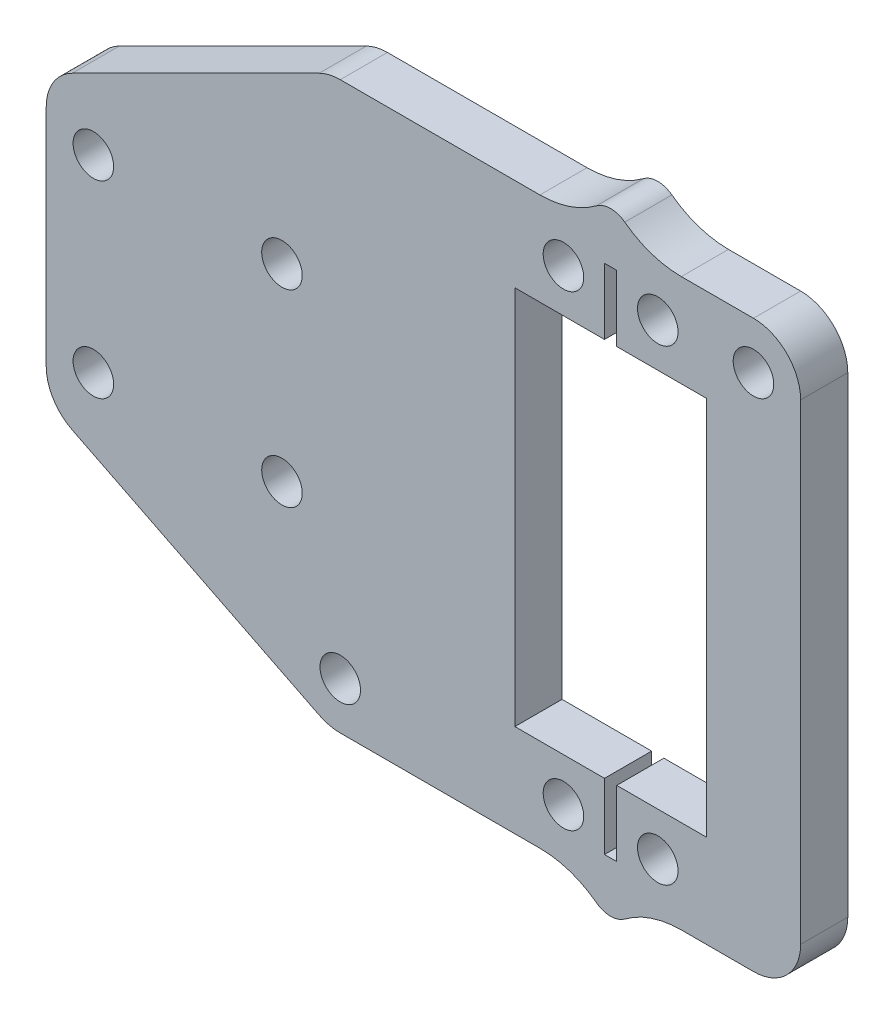
SolidWorks part; units mm, degrees
material "ﾎﾟﾘｴﾁﾚﾝｲﾐﾝ(PEI)"
ref_plane "正面" through (0, 0, 0) normal (0, 0, 1) x (1, 0, 0)
ref_plane "平面" through (0, 0, 0) normal (0, 1, 0) x (1, 0, 0)
ref_plane "右側面" through (0, 0, 0) normal (1, 0, 0) x (0, 0, -1)
sketch "ｽｹｯﾁ1" plane through (0, 0, 0) normal (0, 0, 1) x (1, 0, 0)
  line L0 (0, 24.75) -> (0, -24.75) construction
  line L1 (-5, 24.75) -> (5, 24.75) construction
  line L2 (-5, 24.75) -> (-5, -24.75) construction
  line L3 (-5, -24.75) -> (5, -24.75) construction
  line L4 (5, 24.75) -> (5, -24.75) construction
  line L5 (-5, 24.75) -> (5, -24.75) construction
  line L6 (-5, -24.75) -> (5, 24.75) construction
  line L7 (-5, 0) -> (5, 0) construction
  line L8 (0.65, -27.15) -> (0.65, -20.15)
  line L9 (-10.15, 20.15) -> (10.15, 20.15)
  line L10 (-10.15, 20.15) -> (-10.15, -20.15)
  line L11 (-10.15, -20.15) -> (10.15, -20.15)
  line L12 (10.15, 20.15) -> (10.15, -20.15)
  line L13 (-10.15, 20.15) -> (10.15, -20.15) construction
  line L14 (-10.15, -20.15) -> (10.15, 20.15) construction
  line L15 (-0.65, 27.15) -> (0.65, 27.15)
  line L16 (-0.65, 27.15) -> (-0.65, 20.15)
  line L17 (-0.65, 20.15) -> (0.65, 20.15)
  line L18 (0.65, 27.15) -> (0.65, 20.15)
  line L19 (-0.65, 27.15) -> (0.65, 20.15) construction
  line L20 (-0.65, 20.15) -> (0.65, 27.15) construction
  line L21 (-0.65, -27.15) -> (-0.65, -20.15)
  line L22 (-0.65, -27.15) -> (0.65, -27.15)
  line L23 (10.15, 0) -> (-51.75, 0) construction
  line L25 (-59.85, 30) -> (20.15, 30)
  line L26 (-59.85, 30) -> (-59.85, -30)
  line L27 (-59.85, -30) -> (20.15, -30)
  line L28 (20.15, 30) -> (20.15, -30)
  line L29 (-59.85, 30) -> (20.15, -30) construction
  line L30 (-59.85, -30) -> (20.15, 30) construction
  circle A0 centre (-5, 24.75) radius 2.15
  circle A1 centre (5, 24.75) radius 2.15
  circle A2 centre (5, -24.75) radius 2.15
  circle A3 centre (-5, -24.75) radius 2.15
  point P0 (0, 0)
  point P14 (0, 0)
  point P19 (0, 23.65)
  point P29 (-19.85, 0)
  dimension "D3" = 4.3
  dimension "D1" = 10
  dimension "D2" = 49.5
  dimension "D4" = 20.3
  dimension "D5" = 40.3
  dimension "D6" = 1.3
  dimension "D7" = 7
  dimension "D8" = 60
  dimension "D9" = 10
  dimension "D10" = 80
extrude "ﾎﾞｽ - 押し出し1" add sketch "ｽｹｯﾁ1" along normal blind 5 contours L28 L25 L26 L27 A1 A0 L22 L21 L11 L10 L9 L16 L15 L18 L12 L8 A2 A3
sketch "ｽｹｯﾁ2" plane through (0, 0, 5) normal (0, 0, 1) x (1, 0, 0)
  line L0 (-59.85, 0) -> (20.15, 0) construction
  line L1 (-59.85, 30) -> (-59.85, -30) construction
  line L2 (20.15, 30) -> (20.15, -30) construction
  line L3 (-54.85, 0) -> (-54.85, 10) construction
  line L4 (-54.85, 10) -> (-34.85, 10) construction
  circle A0 centre (-54.85, 10) radius 2.15
  circle A1 centre (-54.85, -10) radius 2.15
  circle A2 centre (-34.85, 10) radius 2.15
  circle A3 centre (-34.85, -10) radius 2.15
  dimension "D1" = 4.3
  dimension "D2" = 5
  dimension "D3" = 20
  dimension "D5" = 20
  dimension "D4" = 2
extrude "ｶｯﾄ - 押し出し1" cut sketch "ｽｹｯﾁ2" against normal through all
sketch "ｽｹｯﾁ3" plane through (0, 0, 5) normal (0, 0, 1) x (1, 0, 0)
  line L0 (-59.85, 30) -> (20.15, 30) construction
  line L1 (20.15, 30) -> (20.15, -30) construction
  line L6 (20.15, -30) -> (20.15, 30)
  line L7 (20.15, 30) -> (-59.85, 30)
  line L8 (-59.85, 30) -> (-59.85, -30)
  line L9 (-59.85, -30) -> (20.15, -30)
  line L10 (20.15, -30) -> (20.15, 30)
  line L11 (20.15, 30) -> (-59.85, 30)
  line L12 (-59.85, 30) -> (-59.85, -30)
  line L13 (-59.85, -30) -> (20.15, -30)
  circle A0 centre (15.15, 25) radius 5
  circle A1 centre (15.15, 25) radius 2.15
  line M12 (20.15, 30) -> (-59.85, 30)
  dimension "D1" = 10
  dimension "D2" = 4.3
  dimension "D3" = 0
extrude "ｶｯﾄ - 押し出し2" cut sketch "ｽｹｯﾁ3" against normal through all contours A1 | A0 L10 M12
sketch "ｽｹｯﾁ4" plane through (0, 0, 5) normal (0, 0, 1) x (1, 0, 0)
  line L0 (0, 0) -> (-59.85, 0) construction
  line L1 (-59.85, 30) -> (-59.85, -30) construction
  line L2 (-59.85, 15.0017) -> (-29.85, 30)
  line L3 (-59.85, 30) -> (15.15, 30) construction
  line L4 (-59.85, -15.0017) -> (-29.85, -30)
  line L9 (20.15, -30) -> (20.15, 25)
  line L10 (15.15, 30) -> (-59.85, 30)
  line L11 (-59.85, 30) -> (-59.85, -30)
  line L12 (-59.85, -30) -> (20.15, -30)
  line L13 (20.15, -30) -> (20.15, 25)
  line L14 (15.15, 30) -> (-59.85, 30)
  line L15 (-59.85, 30) -> (-59.85, -30)
  line L16 (-59.85, -30) -> (20.15, -30)
  arc A1 (20.15, 25) -> (15.15, 30) centre (15.15, 25) ccw
  arc A2 (20.15, 25) -> (15.15, 30) centre (15.15, 25) ccw
  line M31 (15.15, 30) -> (-59.85, 30)
  line M32 (-59.85, 30) -> (-59.85, -30)
  line M33 (-59.85, -30) -> (20.15, -30)
  dimension "D1" = 15.0017
  dimension "D2" = 30
  dimension "D3" = 0
extrude "ｶｯﾄ - 押し出し3" cut sketch "ｽｹｯﾁ4" against normal through all contours L2 M32 M31 | L4 M32 M33
fillet "ﾌｨﾚｯﾄ1" radius 5 1 edges at (20.15, -30, 2.5)
sketch "ｽｹｯﾁ5" plane through (0, 0, 5) normal (0, 0, 1) x (1, 0, 0)
  line L0 (-29.85, -30) -> (15.15, -30) construction
  line L1 (-59.85, -15.0017) -> (-29.85, -30) construction
  circle A0 centre (-28.6698, -25) radius 5 construction
  circle A1 centre (-28.6698, -25) radius 2.15
  dimension "D1" = 10
  dimension "D2" = 4.3
extrude "ｶｯﾄ - 押し出し4" cut sketch "ｽｹｯﾁ5" against normal through all
fillet "ﾌｨﾚｯﾄ2" radius 5 4 edges at (-29.85, -30, 2.5) (-59.85, -15.0017, 2.5) (-29.85, 30, 2.5) (-59.85, 15.0017, 2.5)
sketch "ｽｹｯﾁ6" plane through (0, 0, 5) normal (0, 0, 1) x (1, 0, 0)
  line L0 (0, 0) -> (0, 47.5768) construction
  line L2 (-10.15, 0) -> (10.15, 0) construction
  line L7 (-57.0859, -16.3836) -> (-30.9056, -29.4722)
  line L8 (-28.6698, -30) -> (15.15, -30)
  line L9 (20.15, -25) -> (20.15, 25)
  line L10 (15.15, 30) -> (-28.6698, 30)
  line L11 (-30.9056, 29.4722) -> (-57.0859, 16.3836)
  line L12 (-59.85, 11.9114) -> (-59.85, -11.9114)
  line L13 (-57.0859, -16.3836) -> (-30.9056, -29.4722)
  line L14 (-28.6698, -30) -> (15.15, -30)
  line L15 (20.15, -25) -> (20.15, 25)
  line L16 (15.15, 30) -> (-28.6698, 30)
  line L17 (-30.9056, 29.4722) -> (-57.0859, 16.3836)
  line L18 (-59.85, 11.9114) -> (-59.85, -11.9114)
  line L26 (-0.65, -27.15) -> (0.65, -27.15)
  line L27 (-0.65, -20.15) -> (-0.65, -27.15)
  line L28 (-10.15, -20.15) -> (-0.65, -20.15)
  line L29 (-10.15, 20.15) -> (-10.15, -20.15)
  line L30 (-0.65, 20.15) -> (-10.15, 20.15)
  line L31 (-0.65, 27.15) -> (-0.65, 20.15)
  line L32 (0.65, 27.15) -> (-0.65, 27.15)
  line L33 (0.65, 20.15) -> (0.65, 27.15)
  line L34 (10.15, 20.15) -> (0.65, 20.15)
  line L35 (10.15, -20.15) -> (10.15, 20.15)
  line L36 (0.65, -20.15) -> (10.15, -20.15)
  line L37 (0.65, -27.15) -> (0.65, -20.15)
  line L38 (-0.65, -27.15) -> (0.65, -27.15)
  line L39 (-0.65, -20.15) -> (-0.65, -27.15)
  line L40 (-10.15, -20.15) -> (-0.65, -20.15)
  line L41 (-10.15, 20.15) -> (-10.15, -20.15)
  line L42 (-0.65, 20.15) -> (-10.15, 20.15)
  line L43 (-0.65, 27.15) -> (-0.65, 20.15)
  line L44 (0.65, 27.15) -> (-0.65, 27.15)
  line L45 (0.65, 20.15) -> (0.65, 27.15)
  line L46 (10.15, 20.15) -> (0.65, 20.15)
  line L47 (10.15, -20.15) -> (10.15, 20.15)
  line L48 (0.65, -20.15) -> (10.15, -20.15)
  line L49 (0.65, -27.15) -> (0.65, -20.15)
  circle A0 centre (0, 30) radius 2.5
  circle A1 centre (0, -30) radius 2.5
  circle A2 centre (-28.6698, -25) radius 2.15
  circle A3 centre (-28.6698, -25) radius 2.15
  circle A4 centre (-34.85, 10) radius 2.15
  circle A5 centre (-34.85, 10) radius 2.15
  arc A6 (-30.9056, -29.4722) -> (-28.6698, -30) centre (-28.6698, -25) ccw
  arc A7 (15.15, -30) -> (20.15, -25) centre (15.15, -25) ccw
  arc A8 (20.15, 25) -> (15.15, 30) centre (15.15, 25) ccw
  arc A9 (-28.6698, 30) -> (-30.9056, 29.4722) centre (-28.6698, 25) ccw
  arc A10 (-57.0859, 16.3836) -> (-59.85, 11.9114) centre (-54.85, 11.9114) ccw
  arc A11 (-59.85, -11.9114) -> (-57.0859, -16.3836) centre (-54.85, -11.9114) ccw
  arc A12 (-30.9056, -29.4722) -> (-28.6698, -30) centre (-28.6698, -25) ccw
  arc A13 (15.15, -30) -> (20.15, -25) centre (15.15, -25) ccw
  arc A14 (20.15, 25) -> (15.15, 30) centre (15.15, 25) ccw
  arc A15 (-28.6698, 30) -> (-30.9056, 29.4722) centre (-28.6698, 25) ccw
  arc A16 (-57.0859, 16.3836) -> (-59.85, 11.9114) centre (-54.85, 11.9114) ccw
  arc A17 (-59.85, -11.9114) -> (-57.0859, -16.3836) centre (-54.85, -11.9114) ccw
  circle A18 centre (-34.85, -10) radius 2.15
  circle A19 centre (-34.85, -10) radius 2.15
  circle A20 centre (-54.85, 10) radius 2.15
  circle A21 centre (-54.85, 10) radius 2.15
  circle A22 centre (5, 24.75) radius 2.15
  circle A23 centre (5, 24.75) radius 2.15
  circle A24 centre (-5, 24.75) radius 2.15
  circle A25 centre (-5, 24.75) radius 2.15
  circle A26 centre (5, -24.75) radius 2.15
  circle A27 centre (5, -24.75) radius 2.15
  circle A28 centre (-5, -24.75) radius 2.15
  circle A29 centre (-5, -24.75) radius 2.15
  circle A30 centre (-54.85, -10) radius 2.15
  circle A31 centre (-54.85, -10) radius 2.15
  circle A32 centre (15.15, 25) radius 2.15
  circle A33 centre (15.15, 25) radius 2.15
  dimension "D2" = 5
  dimension "D1" = 0
  dimension "D3" = 0
  dimension "D4" = 0
  dimension "D5" = 0
  dimension "D6" = 0
  dimension "D7" = 0
  dimension "D8" = 0
  dimension "D9" = 0
  dimension "D10" = 0
  dimension "D11" = 0
  dimension "D12" = 0
  dimension "D13" = 0
extrude "ﾎﾞｽ - 押し出し2" add sketch "ｽｹｯﾁ6" against normal blind 5 contours L16 A0 | A1 L14
fillet "ﾌｨﾚｯﾄ3" radius 10 4 edges at (-2.5, -30, 2.5) (2.5, -30, 2.5) (2.5, 30, 2.5) (-2.5, 30, 2.5)
